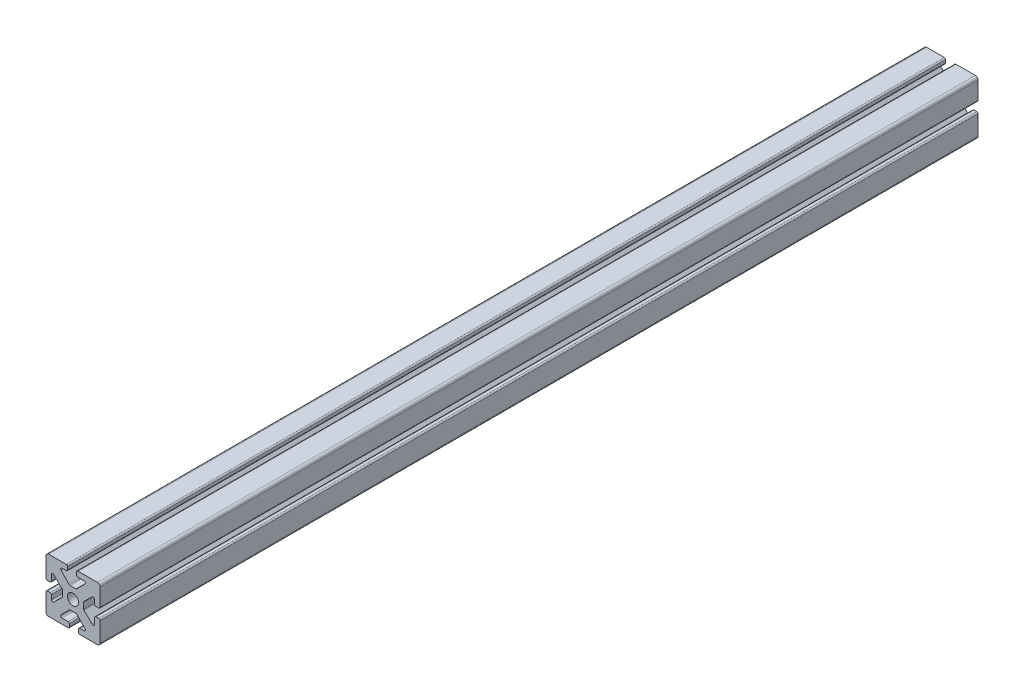
SolidWorks part; units mm, degrees
ref_plane "Front" through (0, 0, 0) normal (0, 0, 1) x (1, 0, 0)
ref_plane "Top" through (0, 0, 0) normal (0, 1, 0) x (1, 0, 0)
ref_plane "Right" through (0, 0, 0) normal (1, 0, 0) x (0, 0, -1)
sketch "草图1" plane through (0, 0, 0) normal (0, 0, 1) x (1, 0, 0)
  line L1 (-20, 20) -> (20, 20)
  line L2 (-20, 20) -> (-20, -20)
  line L3 (-20, -20) -> (20, -20)
  line L4 (20, 20) -> (20, -20)
  line L5 (-20, 20) -> (20, -20) construction
  line L6 (-20, -20) -> (20, 20) construction
  point P0 (0, 0)
  dimension "D1" = 40
extrude "凸台-拉伸1" add sketch "草图1" along normal blind 650
sketch "草图2" plane through (0, 0, 650) normal (0, 0, 1) x (1, 0, 0)
  circle A0 centre (0, 0) radius 4.05
  dimension "D1" = 8.1
extrude "切除-拉伸1" cut sketch "草图2" against normal blind 10000
sketch "草图4" plane through (0, 0, 650) normal (0, 0, 1) x (1, 0, 0)
  line L0 (20, -20) -> (20, 20) construction
  line L1 (20, 0) -> (20, 4)
  line L2 (20, 0) -> (20, -2.652)
  line L3 (7.8769, 2.6) -> (7.8769, -2.6)
  line L4 (20, 4) -> (16, 4)
  line L5 (20, -2.652) -> (16, -2.652)
  line L6 (16, 10.5) -> (16, 4)
  line L7 (16, 10.5) -> (7.8769, 2.6)
  line L8 (16, -10.5) -> (7.8769, -2.6)
  line L9 (16, -2.652) -> (16, -10.5)
  point P11 (7.8769, 0)
  point P12 (16, 0)
extrude "切除-拉伸2" cut sketch "草图4" against normal blind 10000
fillet "圆角1" radius 1 8 edges at (16, 10.5, 325) (16, -10.5, 325) (7.8769, 2.6, 325) (20, -2.652, 325) (16, -2.652, 325) (20, 4, 325) (16, 4, 325) (7.8769, -2.6, 325)
pattern_circular "阵列(圆周)2" count 4 over 360 about axis through (0, 0, 0) along (0, 0, 1) of "切除-拉伸2"
fillet "圆角2" radius 1 8 edges at (10.5, 16, 325) (-10.5, 16, 325) (-4, 20, 325) (2.652, 16, 325) (2.652, 20, 325) (-2.6, 7.8769, 325) (-4, 16, 325) (2.6, 7.8769, 325)
fillet "圆角3" radius 1 8 edges at (-7.8769, -2.6, 325) (-7.8769, 2.6, 325) (-20, 2.652, 325) (-16, 10.5, 325) (-20, -4, 325) (-16, -4, 325) (-16, -10.5, 325) (-16, 2.652, 325)
fillet "圆角4" radius 1 8 edges at (4, -20, 325) (4, -16, 325) (10.5, -16, 325) (-2.652, -20, 325) (2.6, -7.8769, 325) (-2.6, -7.8769, 325) (-2.652, -16, 325) (-10.5, -16, 325)
fillet "圆角5" radius 2 4 edges at (-20, -20, 325) (20, -20, 325) (-20, 20, 325) (20, 20, 325)
